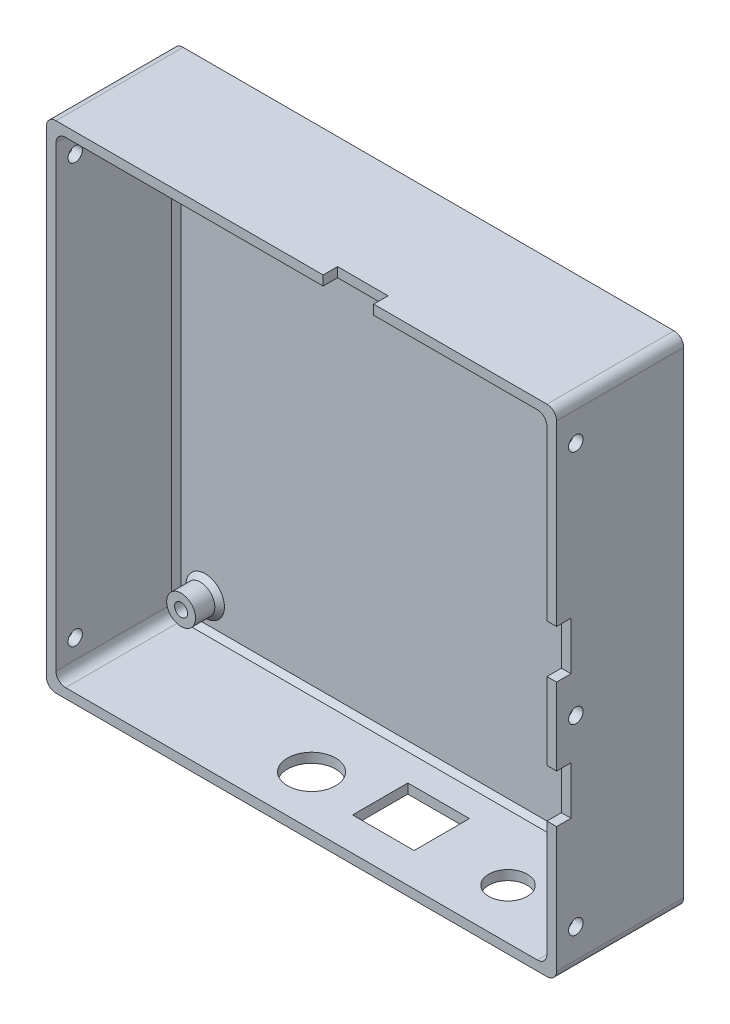
SolidWorks part; units mm, degrees
ref_plane "Спереди" through (0, 0, 0) normal (0, 0, 1) x (1, 0, 0)
ref_plane "Сверху" through (0, 0, 0) normal (0, 1, 0) x (1, 0, 0)
ref_plane "Справа" through (0, 0, 0) normal (1, 0, 0) x (0, 0, -1)
other "Configuration Table"
sketch "Эскиз1" plane through (0, 0, 0) normal (0, 0, 1) x (1, 0, 0)
  line L5 (-53, -51.5) -> (53, -51.5)
  line L6 (-53, -51.5) -> (-53, 51.5)
  line L11 (-53, 51.5) -> (53, 51.5)
  line L12 (53, -51.5) -> (53, 51.5)
  line L13 (-53, -51.5) -> (53, 51.5) construction
  line L14 (-53, 51.5) -> (53, -51.5) construction
  line L15 (-51, -49.5) -> (51, -49.5)
  line L16 (-51, -49.5) -> (-51, 49.5)
  line L17 (-51, 49.5) -> (51, 49.5)
  line L18 (51, -49.5) -> (51, 49.5)
  line L19 (-51, -49.5) -> (51, 49.5) construction
  line L20 (-51, 49.5) -> (51, -49.5) construction
  point P0 (0, 0)
  point P6 (0, 0)
  dimension "D1" = 103
  dimension "D2" = 106
  dimension "D3" = 2
  dimension "D4" = 2
extrude "Бобышка-Вытянуть1" add sketch "Эскиз1" along normal blind 25
sketch "Эскиз2" plane through (0, 0, 0) normal (0, 0, -1) x (-1, 0, 0)
  line L4 (-53, 51.5) -> (-53, -51.5)
  line L5 (-53, -51.5) -> (53, -51.5)
  line L6 (53, -51.5) -> (53, 51.5)
  line L7 (53, 51.5) -> (-53, 51.5)
  line L8 (-53, 51.5) -> (-53, -51.5)
  line L9 (-53, -51.5) -> (53, -51.5)
  line L10 (53, -51.5) -> (53, 51.5)
  line L11 (53, 51.5) -> (-53, 51.5)
  dimension "D1" = 0
extrude "Бобышка-Вытянуть2" add sketch "Эскиз2" along normal blind 1.4
sketch "Эскиз3" plane through (0, 0, 0) normal (0, 0, 1) x (1, 0, 0)
  line L0 (0, 51.5) -> (0, -51.5) construction
  line L1 (-45, -43.5) -> (45, -43.5) construction
  line L2 (-45, -43.5) -> (-45, 39.5) construction
  line L3 (-45, 39.5) -> (45, 39.5) construction
  line L4 (45, -43.5) -> (45, 39.5) construction
  line L5 (-45, -43.5) -> (45, 39.5) construction
  line L6 (-45, 39.5) -> (45, -43.5) construction
  line L7 (53, 51.5) -> (-53, 51.5) construction
  line L8 (-53, -51.5) -> (53, -51.5) construction
  circle A0 centre (-45, 39.5) radius 3
  circle A1 centre (45, 39.5) radius 3
  circle A2 centre (-45, -43.5) radius 3
  circle A3 centre (45, -43.5) radius 3
  circle A4 centre (-45, 39.5) radius 1.35
  circle A5 centre (45, 39.5) radius 1.35
  circle A6 centre (-45, -43.5) radius 1.35
  circle A7 centre (45, -43.5) radius 1.35
  point P0 (-2.3667, -6.7481)
  point P14 (0, -2)
  dimension "D3" = 6
  dimension "D4" = 2.7
  dimension "D1" = 90
  dimension "D2" = 83
  dimension "D5" = 8
extrude "Бобышка-Вытянуть3" add sketch "Эскиз3" along normal blind 5
sketch "Эскиз4" plane through (0, -51.5, 0) normal (0, -1, 0) x (1, 0, 0)
  line L0 (53, 25) -> (53, -1.4) construction
  line L1 (3.7, 18.1) -> (16.5, 18.1)
  line L2 (3.7, 18.1) -> (3.7, 6.6)
  line L3 (3.7, 6.6) -> (16.5, 6.6)
  line L4 (16.5, 18.1) -> (16.5, 6.6)
  line L5 (53, -1.4) -> (-53, -1.4) construction
  dimension "D1" = 36.5
  dimension "D2" = 12.8
  dimension "D3" = 11.5
  dimension "D4" = 8
extrude "Вырез-Вытянуть1" cut sketch "Эскиз4" against normal up to surface (101 mm away) up to face at (0, 49.5, 12.5)
fillet "Скругление1" radius 2 8 edges at (-53, -51.5, 11.8) (53, -51.5, 11.8) (53, 51.5, 11.8) (-53, 51.5, 11.8) (-51, -49.5, 12.5) (-51, 49.5, 12.5) (51, 49.5, 12.5) (51, -49.5, 12.5)
chamfer "Фаска1" distance 1 angle 45 12 edges at (-50.4142, 48.9142, 0) (0, 49.5, 0) (50.4142, 48.9142, 0) (51, 0, 0) (50.4142, -48.9142, 0) (0, -49.5, 0) (-50.4142, -48.9142, 0) (-51, 0, 0) (-48, 39.5, 0) (42, 39.5, 0) (-48, -43.5, 0) (42, -43.5, 0)
sketch "Эскиз5" plane through (0, -51.5, 0) normal (0, -1, 0) x (1, 0, 0)
  line L0 (3.7, 14.6) -> (48.1817, 14.6) construction
  line L1 (3.7, 18.1) -> (3.7, 6.6) construction
  line L2 (3.7, 14.6) -> (-48.4627, 14.6) construction
  line L3 (16.5, 6.6) -> (16.5, 18.1) construction
  line L4 (51, -1.4) -> (-51, -1.4) construction
  circle A0 centre (32.5, 14.6) radius 4
  circle A1 centre (-8.3, 14.6) radius 5
  dimension "D1" = 8
  dimension "D4" = 10
  dimension "D2" = 16
  dimension "D3" = 12
  dimension "D5" = 16
extrude "Вырез-Вытянуть2" cut sketch "Эскиз5" against normal up to surface (2 mm away) up to face at (10.1, -49.5, 12.35)
sketch "Эскиз6" plane through (53, 0, 0) normal (1, 0, 0) x (0, 0, -1)
  line L0 (-25, -49.5) -> (-25, 49.5) construction
  line L1 (-25, -13.5) -> (-22, -13.5)
  line L2 (-25, -13.5) -> (-25, -23.5)
  line L3 (-25, -23.5) -> (-22, -23.5)
  line L4 (-22, -13.5) -> (-22, -23.5)
  line L5 (1.4, -51.5) -> (-25, -51.5) construction
  line L6 (-25, 12.5) -> (-22, 12.5)
  line L7 (-25, 12.5) -> (-25, 2.5)
  line L8 (-25, 2.5) -> (-22, 2.5)
  line L9 (-22, 12.5) -> (-22, 2.5)
  dimension "D1" = 3
  dimension "D2" = 28
  dimension "D3" = 16
  dimension "D4" = 10
extrude "Вырез-Вытянуть3" cut sketch "Эскиз6" against normal up to surface (2 mm away) up to face at (51, 0, 13)
sketch "Эскиз8" plane through (53, 0, 0) normal (1, 0, 0) x (0, 0, -1)
  line L0 (-21, 51.5) -> (-21, -51.2985) construction
  line L1 (-25, 51.5) -> (1.4, 51.5) construction
  line L2 (-25, 12.5) -> (-25, 49.5) construction
  line L3 (1.4, -51.5) -> (-25, -51.5) construction
  circle A0 centre (-21, 43.5) radius 1.5
  circle A1 centre (-21, -43.5) radius 1.5
  dimension "D4" = 3
  dimension "D1" = 4
  dimension "D2" = 8
  dimension "D3" = 8
extrude "Вырез-Вытянуть4" cut sketch "Эскиз8" against normal through all
sketch "Эскиз9" plane through (53, 0, 0) normal (1, 0, 0) x (0, 0, -1)
  line L0 (-21, 43.5) -> (-21, -43.5) construction
  line L1 (1.4, -51.5) -> (-25, -51.5) construction
  circle A0 centre (-21, -5.5) radius 1.5
  dimension "D1" = 3
  dimension "D2" = 46
extrude "Вырез-Вытянуть5" cut sketch "Эскиз9" against normal up to surface (2 mm away) up to face at (51, 43.5, 22.5)
sketch "Эскиз10" plane through (0, 51.5, 0) normal (0, 1, 0) x (1, 0, 0)
  line L0 (51, -25) -> (-51, -25) construction
  line L1 (4.5, -25) -> (15, -25)
  line L2 (4.5, -25) -> (4.5, -22)
  line L3 (4.5, -22) -> (15, -22)
  line L4 (15, -25) -> (15, -22)
  line L5 (53, -22) -> (53, -25) construction
  line L6 (53, 1.4) -> (53, -25) construction
  dimension "D1" = 10.5
  dimension "D2" = 38
extrude "Вырез-Вытянуть6" cut sketch "Эскиз10" against normal up to surface (2 mm away) up to face at (0, 49.5, 13)
